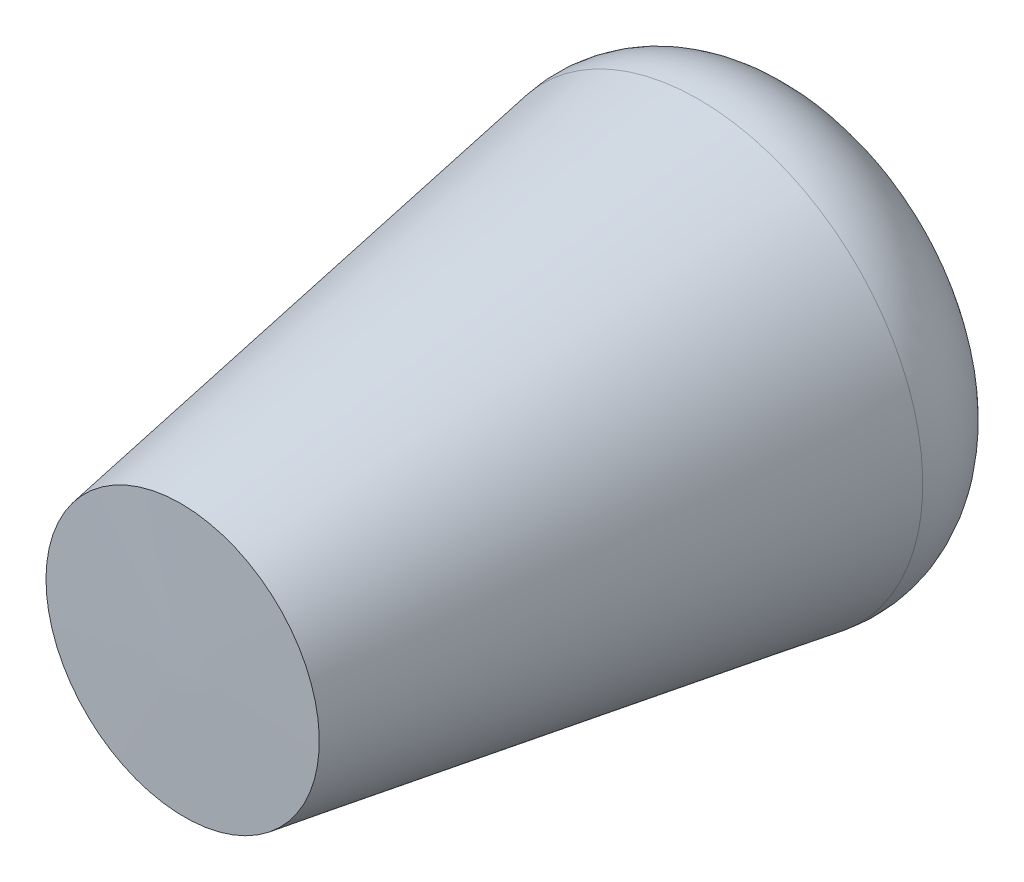
SolidWorks part; units mm, degrees
ref_plane "Front Plane" through (0, 0, 0) normal (0, 0, 1) x (1, 0, 0)
ref_plane "Top Plane" through (0, 0, 0) normal (0, 1, 0) x (1, 0, 0)
ref_plane "Right Plane" through (0, 0, 0) normal (1, 0, 0) x (0, 0, -1)
sketch "Sketch1" plane through (0, 0, 0) normal (1, 0, 0) x (0, 0, -1)
  line L0 (0, 0) -> (0, 4.35)
  line L1 (0, 4.35) -> (16.4806, 7.256)
  line L2 (19.9984, 4.1639) -> (19.9984, 0.256)
  line L3 (19.9984, 0.256) -> (0, 0)
  line L4 (25.2082, 7.256) -> (-5.5836, 7.256) construction
  arc A0 (19.9984, 4.1639) -> (16.4806, 7.256) centre (17.0015, 4.3015) ccw
  dimension "D4" = 3
  dimension "D1" = 7
  dimension "D2" = 4.35
  dimension "D3" = 20
  dimension "D5" = 10
revolve "Revolve1" add sketch "Sketch1" angle 360 about L3
